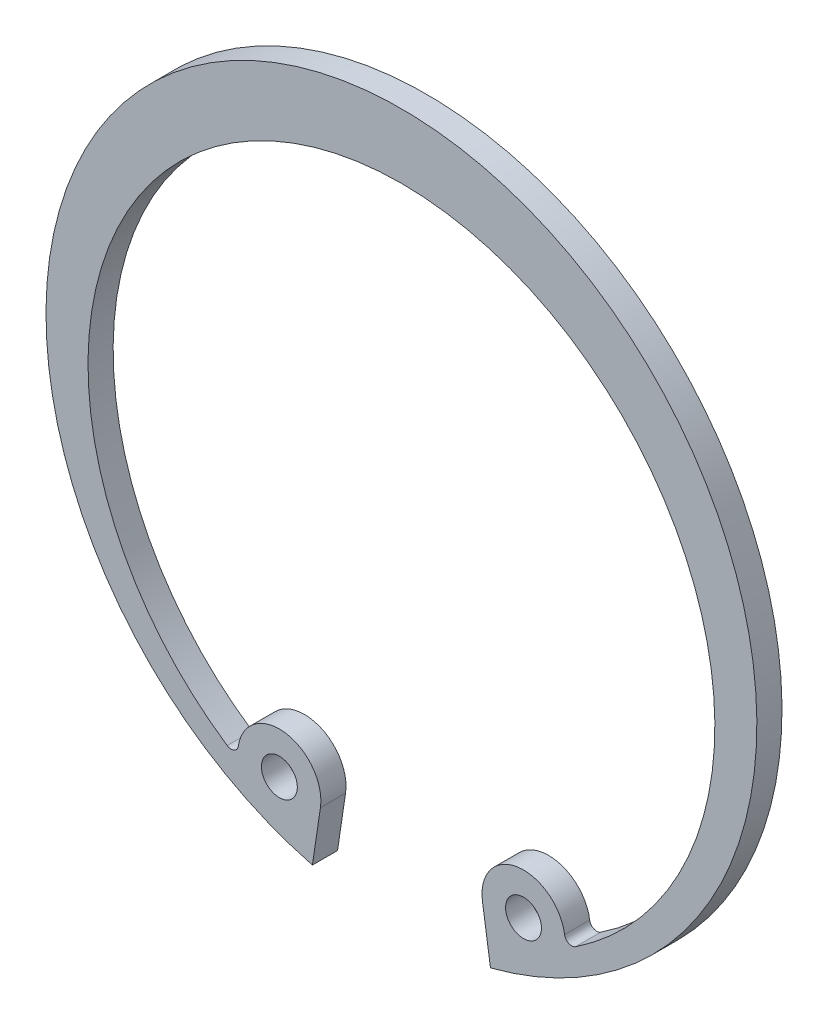
SolidWorks part; units mm, degrees
ref_plane "Front Plane" through (0, 0, 0) normal (0, 0, 1) x (1, 0, 0)
ref_plane "Top Plane" through (0, 0, 0) normal (0, 1, 0) x (1, 0, 0)
ref_plane "Right Plane" through (0, 0, 0) normal (1, 0, 0) x (0, 0, -1)
sketch "Sketch1" plane through (0, 0, 0) normal (0, 0, 1) x (1, 0, 0)
  line L0 (0, 0) -> (0, 24.75) construction
  line L1 (-5.6409, -20.2201) -> (-6.2, -23.9609)
  line L2 (5.6409, -20.2201) -> (6.2, -23.9609)
  line L3 (7.3593, -17.1366) -> (9.7663, -22.7416) construction
  arc A0 (6.2, -23.9609) -> (-6.2, -23.9609) centre (0, 0) ccw
  arc A1 (-12.1329, -19.7167) -> (-11.3603, -19.3736) centre (-11.855, -19.3011) ccw
  circle A2 centre (-8.5, -19.7928) radius 1.25
  circle A3 centre (8.5, -19.7928) radius 1.25
  circle A4 centre (0, 0) radius 17 construction
  arc A6 (-5.6409, -20.2201) -> (-11.3603, -19.3736) centre (-8.5, -19.7928) ccw
  arc A7 (11.3603, -19.3736) -> (5.6409, -20.2201) centre (8.5, -19.7928) ccw
  arc A8 (12.1329, -19.7167) -> (-12.1329, -19.7167) centre (0, -1.575) ccw
  arc A9 (12.1329, -19.7167) -> (11.3603, -19.3736) centre (11.855, -19.3011) cw
  point P13 (0, 20.25)
  dimension "RIC_D2_s" = 49.5
  dimension "RIC_D0_s" = 2.5
  dimension "D1" = 0.5
  dimension "RIC_D5_s" = 34
  dimension "RIC_MSM_2" = 17
  dimension "D2" = 17
  dimension "RIC_MSM_1" = 12.4
  dimension "RIC_B_s" = 4.5
  dimension "RIC_A_s" = 6.1
extrude "Boss-Extrude1" add sketch "Sketch1" along normal blind 1.75
equation "\"RIC_D4_s@Sketch1\"=\"RIC_D2_s@Sketch1\"-1.3*\"RIC_B_s@Sketch1\""
